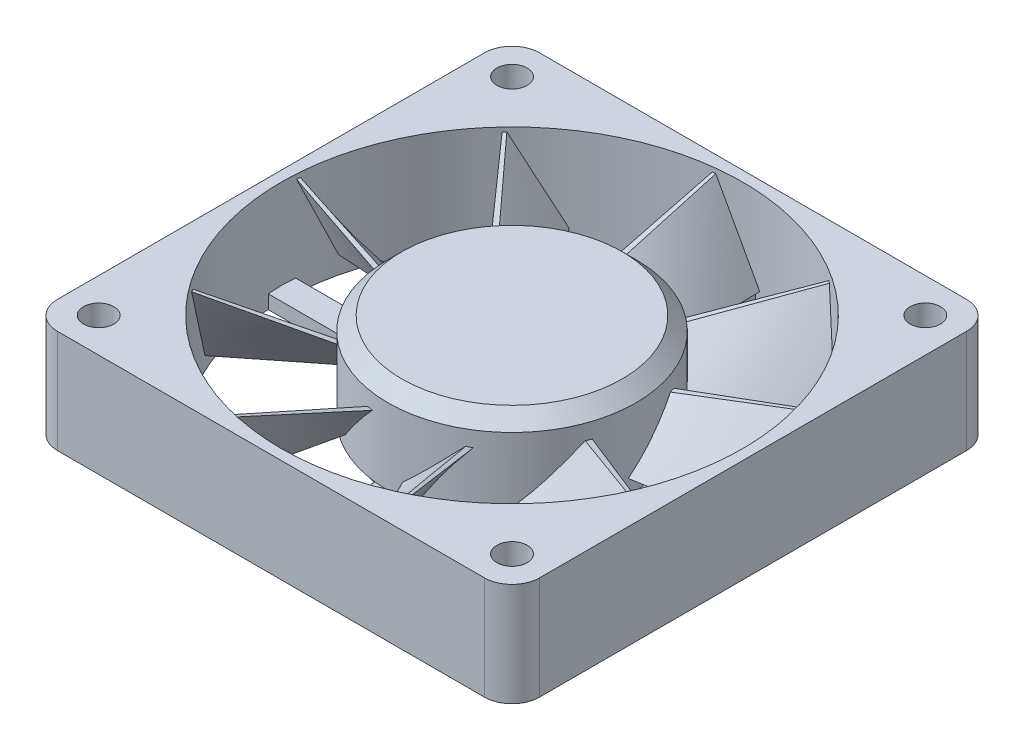
SolidWorks part; units mm, degrees
ref_plane "Front Plane" through (0, 0, 0) normal (0, 0, 1) x (1, 0, 0)
ref_plane "Top Plane" through (0, 0, 0) normal (0, 1, 0) x (1, 0, 0)
ref_plane "Right Plane" through (0, 0, 0) normal (1, 0, 0) x (0, 0, -1)
sketch "Sketch1" plane through (0, 0, 0) normal (0, 1, 0) x (1, 0, 0)
  line L1 (-31, 35) -> (31, 35)
  line L2 (-35, 31) -> (-35, -31)
  line L3 (-31, -35) -> (31, -35)
  line L4 (35, 31) -> (35, -31)
  circle A0 centre (0, 0) radius 33.5
  circle A1 centre (-30, 30) radius 2.2
  circle A2 centre (30, 30) radius 2.2
  circle A3 centre (30, -30) radius 2.2
  circle A4 centre (-30, -30) radius 2.2
  arc A5 (31, -35) -> (35, -31) centre (31, -31) ccw
  arc A6 (31, 35) -> (35, 31) centre (31, 31) cw
  arc A7 (-31, 35) -> (-35, 31) centre (-31, 31) ccw
  arc A8 (-35, -31) -> (-31, -35) centre (-31, -31) ccw
  point P17 (35, -35)
  point P20 (35, 35)
  point P23 (-35, 35)
  dimension "D1" = 67
  dimension "D2" = 30
  dimension "D8" = 4
  dimension "D3" = 30
  dimension "D4" = 35
  dimension "D5" = 35
  dimension "D6" = 70
  dimension "D7" = 70
extrude "Boss-Extrude1" add sketch "Sketch1" along normal blind 15
sketch "Sketch2" plane through (0, 0, 0) normal (0, 1, 0) x (1, 0, 0)
  line L0 (-1.9855, 33.3801) -> (0, 33.5)
  line L1 (0, 33.5) -> (1.9855, 33.3801)
  line L2 (33.3801, 1.9855) -> (33.5, 0)
  line L3 (33.5, 0) -> (33.3801, -1.9855)
  line L4 (-16.3801, 1.9855) -> (-33.3801, 1.9855)
  line L5 (-16.3801, -1.9855) -> (-33.3801, -1.9855)
  line L6 (1.9855, 16.3801) -> (1.9855, 33.3801)
  line L7 (16.3801, -1.9855) -> (33.3801, -1.9855)
  line L8 (-1.9855, -16.3801) -> (-1.9855, -33.3801)
  line L9 (-1.9855, 16.3801) -> (-1.9855, 33.3801)
  line L10 (16.3801, 1.9855) -> (33.3801, 1.9855)
  line L11 (1.9855, -16.3801) -> (1.9855, -33.3801)
  line L12 (-1.9855, -33.3801) -> (0, -33.5)
  line L13 (0, -33.5) -> (1.9855, -33.3801)
  line L14 (-33.3801, -1.9855) -> (-33.5, 0)
  line L15 (-33.5, 0) -> (-33.3801, 1.9855)
  arc A0 (-16.3801, -1.9855) -> (-1.9855, -16.3801) centre (0, 0) ccw
  circle A1 centre (0, 0) radius 33.5 construction
  arc A2 (-1.9855, 16.3801) -> (-16.3801, 1.9855) centre (0, 0) ccw
  arc A3 (16.3801, 1.9855) -> (1.9855, 16.3801) centre (0, 0) ccw
  arc A4 (1.9855, -16.3801) -> (16.3801, -1.9855) centre (0, 0) ccw
extrude "Boss-Extrude2" add sketch "Sketch2" along normal blind 2 separate body
sketch "Sketch3" plane through (0, 2, 0) normal (0, 1, 0) x (1, 0, 0)
  circle A0 centre (0, 0) radius 18
  dimension "D1" = 36
extrude "Boss-Extrude3" add sketch "Sketch3" along normal blind 13
chamfer "Chamfer1" distance 2 angle 45 1 edges at (0, 15, 18)
ref_plane "Plane3" through (0, 0, -33) normal (0, 0, -1) x (-1, 0, 0)
ref_plane "Plane4" through (0, 0, -17) normal (0, 0, -1) x (-1, 0, 0)
sketch "Sketch7" plane through (0, 0, -17) normal (0, 0, -1) x (-1, 0, 0)
  line L1 (3.0038, 10.6159) -> (3.8061, 10.6159)
  line L2 (3.0038, 10.6159) -> (-4.2368, 4.052)
  line L3 (-4.2368, 4.052) -> (-2.1593, 4.052)
  line L4 (3.8061, 10.6159) -> (-2.1593, 4.052)
sketch "Sketch8" plane through (0, 0, -33) normal (0, 0, -1) x (-1, 0, 0)
  line L1 (-2.9643, 2.9629) -> (-1.3827, 2.9629)
  line L2 (-2.9643, 2.9629) -> (3.4194, 14.5929)
  line L3 (3.4194, 14.5929) -> (3.9051, 14.5929)
  line L4 (-1.3827, 2.9629) -> (3.9051, 14.5929)
loft "Loft2" add profiles "Sketch8", "Sketch7"
pattern_circular "CirPattern33" count 9 over 360 about axis through (0, 15, 0) along (0, -1, 0) of "Loft2"
